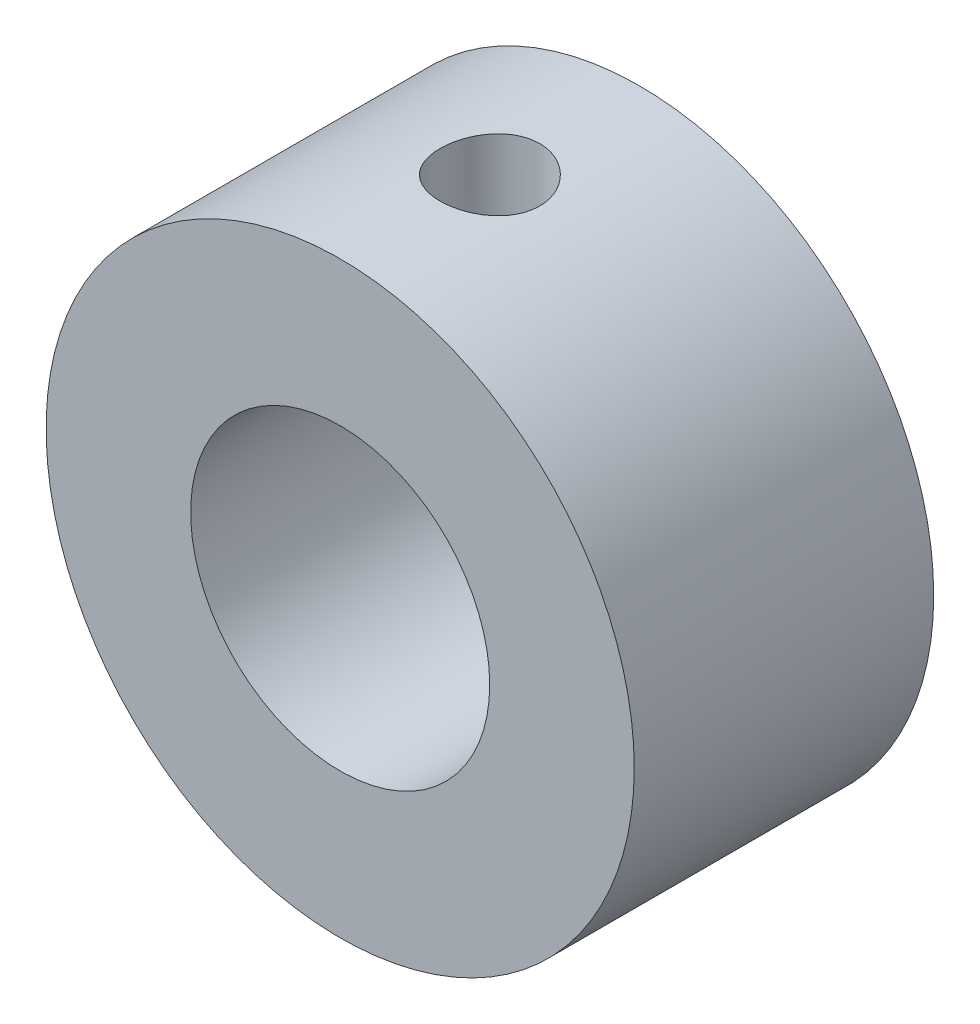
SolidWorks part; units mm, degrees
ref_plane "Front Plane" through (0, 0, 0) normal (0, 0, 1) x (1, 0, 0)
ref_plane "Top Plane" through (0, 0, 0) normal (0, 1, 0) x (1, 0, 0)
ref_plane "Right Plane" through (0, 0, 0) normal (1, 0, 0) x (0, 0, -1)
sketch "Sketch1" plane through (0, 0, 0) normal (0, 0, 1) x (1, 0, 0)
  circle A0 centre (0, 0) radius 4.7625
  circle A1 centre (0, 0) radius 9.3662
  dimension "D1" = 9.525
  dimension "D2" = 18.7325
extrude "Boss-Extrude1" add sketch "Sketch1" along normal blind 9.5377
sketch "Sketch2" plane through (0, 0, 0) normal (0, 0, -1) x (-1, 0, 0)
  line L0 (0, 9.3662) -> (0, 0) construction
  circle A0 centre (0, 0) radius 9.3662 construction
ref_plane "Plane1" through (0, 9.3662, 0) normal (0, 1, 0) x (1, 0, 0)
sketch "Sketch3" plane through (0, 9.3662, 0) normal (0, 1, 0) x (1, 0, 0)
  line L0 (9.3662, 0) -> (-9.3662, 0) construction
  circle A0 centre (0, -4.7688) radius 1.5875
  dimension "D2" = 3.175
  dimension "D1" = 4.7688
extrude "Cut-Extrude1" cut sketch "Sketch3" against normal up to surface (4.6037 mm away)
